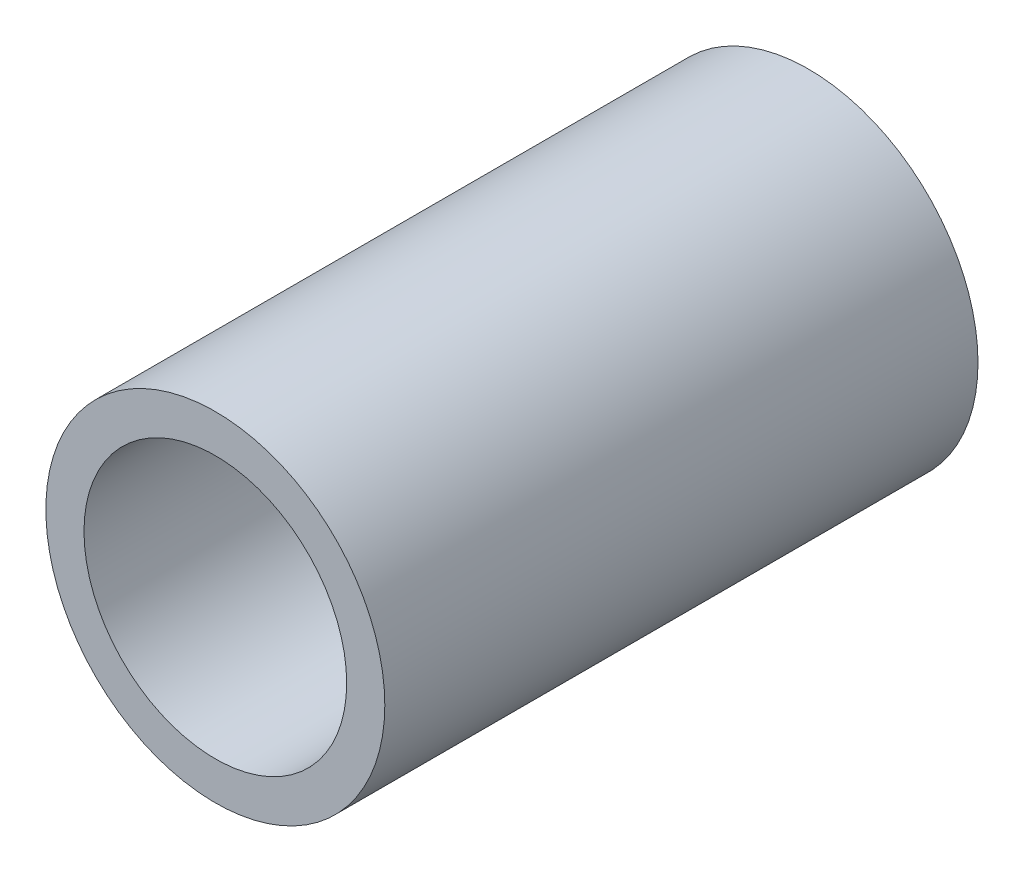
SolidWorks part; units mm, degrees
ref_plane "Спереди" through (0, 0, 0) normal (0, 0, 1) x (1, 0, 0)
ref_plane "Сверху" through (0, 0, 0) normal (0, 1, 0) x (1, 0, 0)
ref_plane "Справа" through (0, 0, 0) normal (1, 0, 0) x (0, 0, -1)
sketch "Эскиз1" plane through (0, 0, 0) normal (0, 0, 1) x (1, 0, 0)
  circle A0 centre (0, 0) radius 1
  circle A1 centre (0, 0) radius 0.775
extrude "Бобышка-Вытянуть1" add sketch "Эскиз1" along normal blind 3.5
